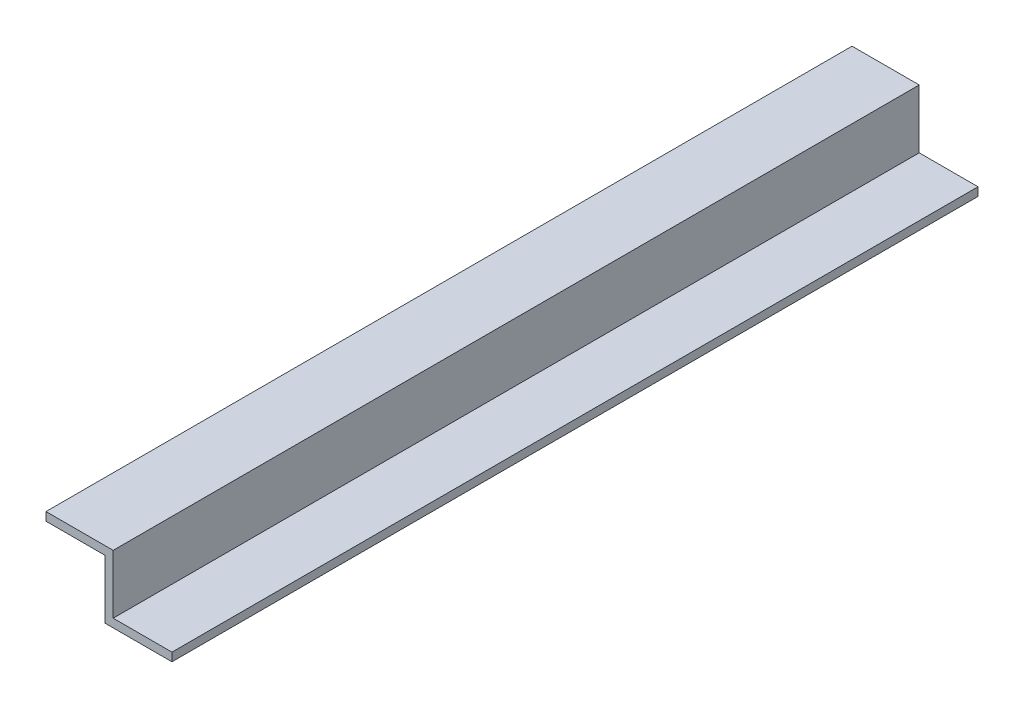
SolidWorks part; units mm, degrees
ref_plane "Front Plane" through (0, 0, 0) normal (0, 0, 1) x (1, 0, 0)
ref_plane "Top Plane" through (0, 0, 0) normal (0, 1, 0) x (1, 0, 0)
ref_plane "Right Plane" through (0, 0, 0) normal (1, 0, 0) x (0, 0, -1)
sketch "Sketch1" plane through (0, 0, 0) normal (0, 0, 1) x (1, 0, 0)
  line L0 (0, -11.1125) -> (0, 11.1125) construction
  line L1 (0, 11.1125) -> (-23.8125, 11.1125) construction
  line L2 (0, -11.1125) -> (23.8125, -11.1125) construction
  line L3 (1.5875, -9.525) -> (23.8125, -9.525) construction
  line L4 (1.5875, -9.525) -> (1.5875, 12.7) construction
  line L5 (1.5875, 12.7) -> (-23.8125, 12.7) construction
  line L6 (-1.5875, -12.7) -> (23.8125, -12.7) construction
  line L7 (-1.5875, -12.7) -> (-1.5875, 9.525) construction
  line L8 (-1.5875, 9.525) -> (-23.8125, 9.525) construction
  line L9 (-23.8125, 12.7) -> (-23.8125, 9.525) construction
  line L10 (23.8125, -9.525) -> (23.8125, -12.7) construction
  point P4 (0, 0)
  dimension "Leg Width" = 25.4
  dimension "Outside Height" = 25.4
  dimension "Wall Thickness" = 3.175
sketch "Sketch2" plane through (0, 0, 0) normal (1, 0, 0) x (0, 0, -1)
  line L0 (152.4, 0) -> (-152.4, 0) construction
  line L1 (0, 0) -> (0, 12.7) construction
  line L2 (-152.4, 0) -> (-152.4, 12.7) construction
  line L3 (152.4, 0) -> (152.4, 12.7) construction
  point P0 (-114.3, 0)
  point P3 (114.3, 0)
  point P4 (0, 0)
  dimension "D1" = 228.6
  dimension "Length" = 304.8
sketch "Sketch3" plane through (0, 0, 0) normal (0, 0, 1) x (1, 0, 0)
  line L0 (23.8125, -9.525) -> (23.8125, -12.7) construction
  line L1 (1.5875, -9.525) -> (23.8125, -9.525) construction
  line L2 (-1.5875, -12.7) -> (23.8125, -12.7) construction
  line L3 (-1.5875, -12.7) -> (-1.5875, 9.525) construction
  line L4 (1.5875, -9.525) -> (1.5875, 12.7) construction
  line L5 (1.5875, 12.7) -> (-23.8125, 12.7) construction
  line L6 (-23.8125, 12.7) -> (-23.8125, 9.525) construction
  line L7 (-1.5875, 9.525) -> (-23.8125, 9.525) construction
  line L8 (23.8125, -9.525) -> (23.8125, -12.7)
  line L9 (1.5875, -9.525) -> (23.8125, -9.525)
  line L10 (-1.5875, -12.7) -> (23.8125, -12.7)
  line L11 (-1.5875, -12.7) -> (-1.5875, 9.525)
  line L12 (1.5875, -9.525) -> (1.5875, 12.7)
  line L13 (1.5875, 12.7) -> (-23.8125, 12.7)
  line L14 (-23.8125, 12.7) -> (-23.8125, 9.525)
  line L15 (-1.5875, 9.525) -> (-23.8125, 9.525)
extrude "Boss-Extrude1" add sketch "Sketch3" along normal up to vertex (152.4 mm away) and the other way up to vertex (152.4 mm away) up to point (0, 0, 152.4) other way up to point (0, 0, -152.4)
equation "\"D1@Sketch2\"=\"Length@Sketch2\"*0.75"
